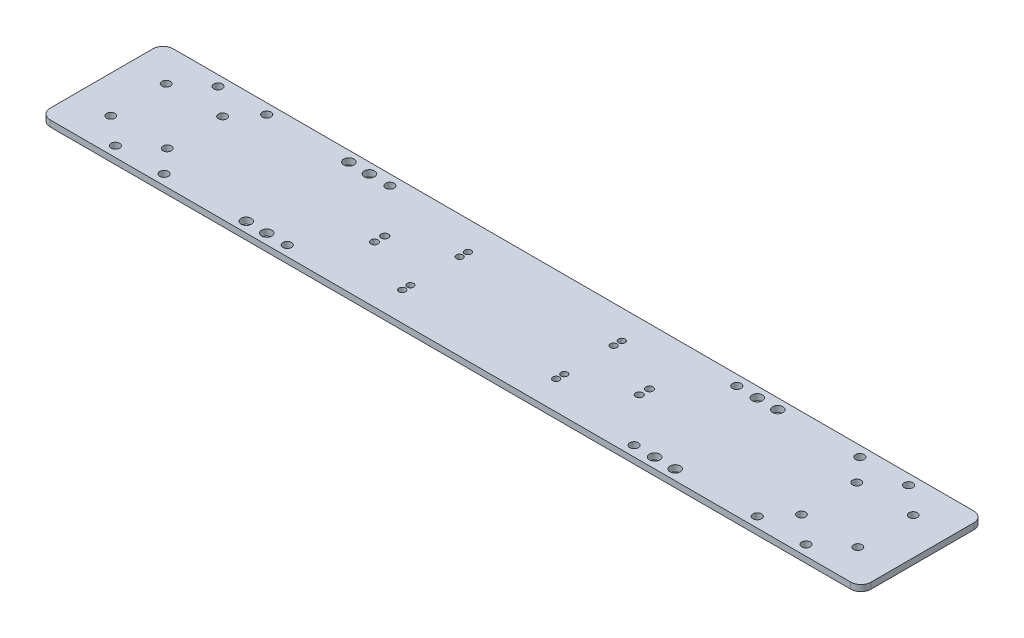
SolidWorks part; units mm, degrees
material "Thornel Mat VMA"
ref_plane "前视基准面" through (0, 0, 0) normal (0, 0, 1) x (1, 0, 0)
ref_plane "上视基准面" through (0, 0, 0) normal (0, 1, 0) x (1, 0, 0)
ref_plane "右视基准面" through (0, 0, 0) normal (1, 0, 0) x (0, 0, -1)
sketch "草图1" plane through (0, 0, 0) normal (0, 1, 0) x (1, 0, 0)
  line L0 (-21.4414, 42.5) -> (-21.4414, 102.5) construction
  line L1 (-221.4414, 42.5) -> (178.5586, 42.5)
  line L2 (-221.4414, 42.5) -> (-221.4414, 102.5)
  line L3 (-221.4414, 102.5) -> (178.5586, 102.5)
  line L4 (178.5586, 42.5) -> (178.5586, 102.5)
  line L5 (-61.4414, 102.5) -> (-61.4414, 168.5)
  line L6 (-61.4414, 168.5) -> (18.5586, 168.5)
  line L7 (18.5586, 168.5) -> (18.5586, 102.5)
  line L8 (-21.4414, 168.5) -> (-21.4414, 102.5) construction
  dimension "D1" = 400
  dimension "D2" = 60
  dimension "D3" = 66
  dimension "D4" = 80
extrude "凸台-拉伸1" add sketch "草图1" along normal blind 3 contours L1 L4 L3 L2
sketch "草图2" plane through (0, 3, 0) normal (0, 1, 0) x (1, 0, 0)
  line L0 (-203.4414, 59) -> (-203.4414, 86) construction
  line L1 (-175.9414, 59) -> (-175.9414, 86) construction
  line L2 (-203.4414, 86) -> (-175.9414, 86) construction
  line L3 (-105.9414, 47.5) -> (-105.9414, 97.5) construction
  line L4 (-189.6914, 86) -> (-189.6914, 102.5) construction
  line L5 (-189.6914, 97.5) -> (-165.9414, 97.5) construction
  line L6 (-221.4414, 72.5) -> (178.5586, 72.5) construction
  line L7 (-221.4414, 42.5) -> (-221.4414, 102.5) construction
  line L8 (178.5586, 42.5) -> (178.5586, 102.5) construction
  line L9 (-203.4414, 72.5) -> (-105.9414, 72.5) construction
  line L10 (-221.4414, 102.5) -> (178.5586, 102.5) construction
  line L11 (-21.4414, 102.5) -> (-21.4414, 42.5) construction
  line L12 (-221.4414, 42.5) -> (178.5586, 42.5) construction
  circle A0 centre (-203.4414, 86) radius 2.05
  circle A1 centre (-203.4414, 59) radius 2.05
  circle A2 centre (-175.9414, 86) radius 2.05
  circle A3 centre (-175.9414, 59) radius 2.05
  circle A4 centre (-105.9414, 97.5) radius 2.1
  circle A5 centre (-165.9414, 97.5) radius 2.1
  circle A6 centre (-105.9414, 47.5) radius 2.1
  circle A7 centre (-165.9414, 47.5) radius 2.1
  circle A8 centre (-189.6914, 97.5) radius 2.1
  circle A9 centre (-189.6914, 47.5) radius 2.1
  circle A10 centre (133.0586, 86) radius 2.05
  circle A11 centre (146.8086, 47.5) radius 2.1
  circle A12 centre (160.5586, 59) radius 2.05
  circle A13 centre (133.0586, 59) radius 2.05
  circle A14 centre (123.0586, 47.5) radius 2.1
  circle A15 centre (63.0586, 47.5) radius 2.1
  circle A16 centre (63.0586, 97.5) radius 2.1
  circle A17 centre (123.0586, 97.5) radius 2.1
  circle A18 centre (146.8086, 97.5) radius 2.1
  circle A19 centre (160.5586, 86) radius 2.05
  point P3 (-203.4414, 72.5)
  point P8 (-175.9414, 72.5)
  point P13 (-105.9414, 72.5)
  dimension "D2" = 4.1
  dimension "D5" = 5
  dimension "D6" = 70
  dimension "D1" = 27
  dimension "D3" = 18
  dimension "D4" = 45.5
extrude "切除-拉伸1" cut sketch "草图2" against normal through all
sketch "草图3" plane through (0, 3, 0) normal (0, 1, 0) x (1, 0, 0)
  line L0 (-21.4414, 102.5) -> (-21.4414, 42.5) construction
  line L1 (-221.4414, 102.5) -> (178.5586, 102.5) construction
  line L2 (-221.4414, 42.5) -> (178.5586, 42.5) construction
  line L3 (-56.7574, 72.5) -> (19.7761, 72.5) construction
  line L4 (-221.4414, 42.5) -> (-221.4414, 102.5) construction
  line L5 (-221.4414, 72.5) -> (178.5586, 72.5) construction
  line L6 (178.5586, 42.5) -> (178.5586, 102.5) construction
  line L7 (-58.9414, 88.5) -> (-58.9414, 56.5) construction
  circle A0 centre (-58.9414, 88.5) radius 1.6
  circle A1 centre (16.0586, 88.5) radius 1.6
  circle A2 centre (16.0586, 56.5) radius 1.6
  circle A3 centre (-58.9414, 56.5) radius 1.6
  circle A4 centre (-58.9414, 84.5) radius 1.6
  circle A5 centre (-58.9414, 60.5) radius 1.6
  circle A6 centre (16.0586, 60.5) radius 1.6
  circle A7 centre (16.0586, 84.5) radius 1.6
  dimension "D1" = 3.2
  dimension "D2" = 37.5
  dimension "D3" = 16
  dimension "D4" = 32
  dimension "D5" = 28
extrude "铰链孔" cut sketch "草图3" against normal blind 10
sketch "草图4" plane through (0, 3, 0) normal (0, 1, 0) x (1, 0, 0)
  line L0 (-221.4414, 72.5) -> (178.5586, 72.5) construction
  line L1 (-221.4414, 42.5) -> (-221.4414, 102.5) construction
  line L2 (178.5586, 42.5) -> (178.5586, 102.5) construction
  line L3 (-21.4414, 102.5) -> (-21.4414, 42.5) construction
  line L4 (-221.4414, 102.5) -> (178.5586, 102.5) construction
  line L5 (-221.4414, 42.5) -> (178.5586, 42.5) construction
  line L6 (-85.9414, 102.5) -> (-85.9414, 42.5) construction
  line L7 (-115.9414, 102.5) -> (-115.9414, 42.5) construction
  line L8 (-165.9414, 47.5) -> (-105.9414, 47.5) construction
  line L9 (-125.9414, 97.5) -> (-115.9414, 97.5) construction
  circle A0 centre (-175.9414, 86) radius 2.05 construction
  circle A1 centre (-85.9414, 75) radius 1.75
  circle A2 centre (-85.9414, 70) radius 1.75
  circle A3 centre (43.0586, 70) radius 1.75
  circle A4 centre (43.0586, 75) radius 1.75
  circle A5 centre (-115.9414, 47.5) radius 2.5
  circle A6 centre (-125.9414, 47.5) radius 2.5
  circle A7 centre (-115.9414, 97.5) radius 2.5
  circle A8 centre (-105.9414, 47.5) radius 2.1 construction
  circle A9 centre (-125.9414, 97.5) radius 2.5
  circle A10 centre (73.0586, 47.5) radius 2.5
  circle A11 centre (83.0586, 47.5) radius 2.5
  circle A12 centre (73.0586, 97.5) radius 2.5
  circle A13 centre (83.0586, 97.5) radius 2.5
  dimension "D2" = 5
  dimension "D3" = 3.5
  dimension "D4" = 10
  dimension "D5" = 10
  dimension "D1" = 90
extrude "切除-拉伸2" cut sketch "草图4" against normal through all
fillet "圆角1" radius 5 4 edges at (178.5586, 1.5, -102.5) (178.5586, 1.5, -42.5) (-221.4414, 1.5, -42.5) (-221.4414, 1.5, -102.5)
